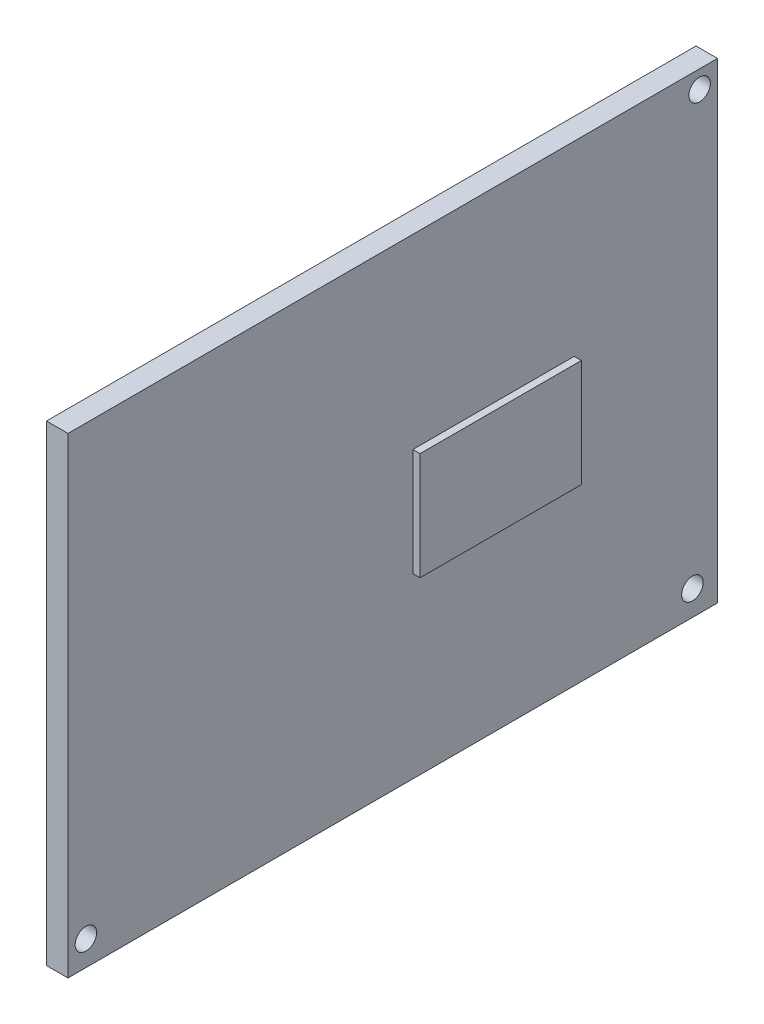
SolidWorks part; units mm, degrees
ref_plane "Alzado" through (0, 0, 0) normal (0, 0, 1) x (1, 0, 0)
ref_plane "Planta" through (0, 0, 0) normal (0, 1, 0) x (1, 0, 0)
ref_plane "Vista lateral" through (0, 0, 0) normal (1, 0, 0) x (0, 0, -1)
sketch "Croquis1" plane through (0, 0, 0) normal (1, 0, 0) x (0, 0, -1)
  line L1 (0, 0) -> (90.62, 0)
  line L2 (0, 0) -> (0, 65.8)
  line L3 (0, 65.8) -> (90.62, 65.8)
  line L4 (90.62, 0) -> (90.62, 65.8)
  circle A0 centre (88.12, 63.3) radius 1.5
  circle A1 centre (87.12, 3.5) radius 1.5
  circle A2 centre (2.5, 3.5) radius 1.5
  point P11 (84.3499, 62.3386)
  dimension "D3" = 3
  dimension "D1" = 90.62
  dimension "D2" = 65.8
  dimension "D4" = 2.5
  dimension "D5" = 2.5
  dimension "D6" = 3.5
  dimension "D7" = 3.5
  dimension "D8" = 3.5
  dimension "D9" = 2.5
extrude "Saliente-Extruir1" add sketch "Croquis1" along normal blind 3
sketch "Croquis2" plane through (3, 0, 0) normal (1, 0, 0) x (0, 0, -1)
  line L0 (90.62, 65.8) -> (0, 65.8) construction
  line L1 (48.12, 39.8) -> (70.62, 39.8)
  line L2 (48.12, 39.8) -> (48.12, 24.8)
  line L3 (48.12, 24.8) -> (70.62, 24.8)
  line L4 (70.62, 39.8) -> (70.62, 24.8)
  line L5 (90.62, 0) -> (90.62, 65.8) construction
  dimension "D1" = 22.5
  dimension "D2" = 15
  dimension "D3" = 26
  dimension "D4" = 20
extrude "Saliente-Extruir2" add sketch "Croquis2" along normal blind 1
